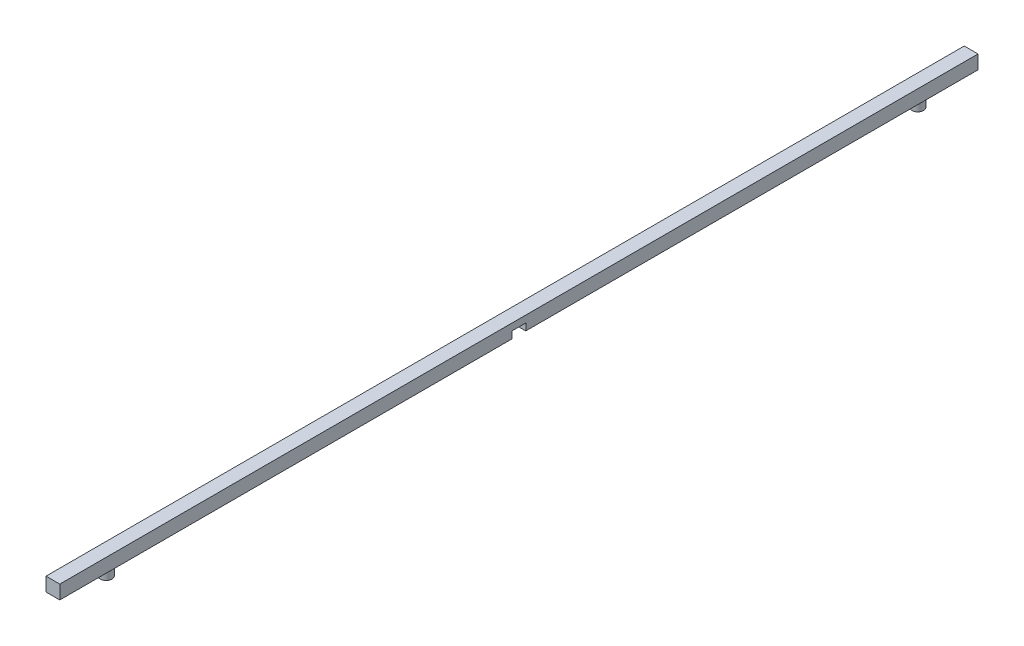
SolidWorks part; units mm, degrees
ref_plane "前视基准面" through (0, 0, 0) normal (0, 0, 1) x (1, 0, 0)
ref_plane "上视基准面" through (0, 0, 0) normal (0, 1, 0) x (1, 0, 0)
ref_plane "右视基准面" through (0, 0, 0) normal (1, 0, 0) x (0, 0, -1)
sketch "草图1" plane through (0, 0, 0) normal (1, 0, 0) x (0, 0, -1)
  line L0 (-1000, 30) -> (1000, 30)
  line L1 (1000, 30) -> (1000, 0)
  line L2 (1000, 0) -> (15, 0)
  line L3 (-1000, 0) -> (-1000, 30)
  line L4 (-15, 0) -> (-15, 15)
  line L5 (-15, 15) -> (15, 15)
  line L6 (15, 15) -> (15, 0)
  line L7 (0, 109.6295) -> (0, -69.072) construction
  line L8 (-15, 0) -> (-1000, 0)
  dimension "D1" = 2000
  dimension "D2" = 30
  dimension "D3" = 30
  dimension "D4" = 15
extrude "凸台-拉伸1" add sketch "草图1" along normal blind 30
sketch "草图2" plane through (0, 0, 0) normal (0, -1, 0) x (1, 0, 0)
  line L0 (378.7085, 0) -> (-306.5824, 0) construction
  line L1 (0, 1000) -> (0, 15) construction
  circle A0 centre (15, 883.8835) radius 10
  circle A1 centre (15, -883.8835) radius 10
  dimension "D1" = 20
  dimension "D2" = 15
  dimension "D3" = 1767.767
extrude "切除-拉伸1" cut sketch "草图2" against normal blind 15
sketch "草图3" plane through (0, 0, 0) normal (0, -1, 0) x (1, 0, 0)
  line L0 (281.0599, 0) -> (-395.0545, 0) construction
  circle A0 centre (15, 883.8835) radius 12.5
  circle A1 centre (15, 883.8835) radius 10
  circle A2 centre (15, 883.8835) radius 10 construction
  circle A3 centre (15, -883.8835) radius 10
  circle A4 centre (15, -883.8835) radius 12.5
  dimension "D1" = 25
extrude "凸台-拉伸2" add sketch "草图3" along normal blind 20
